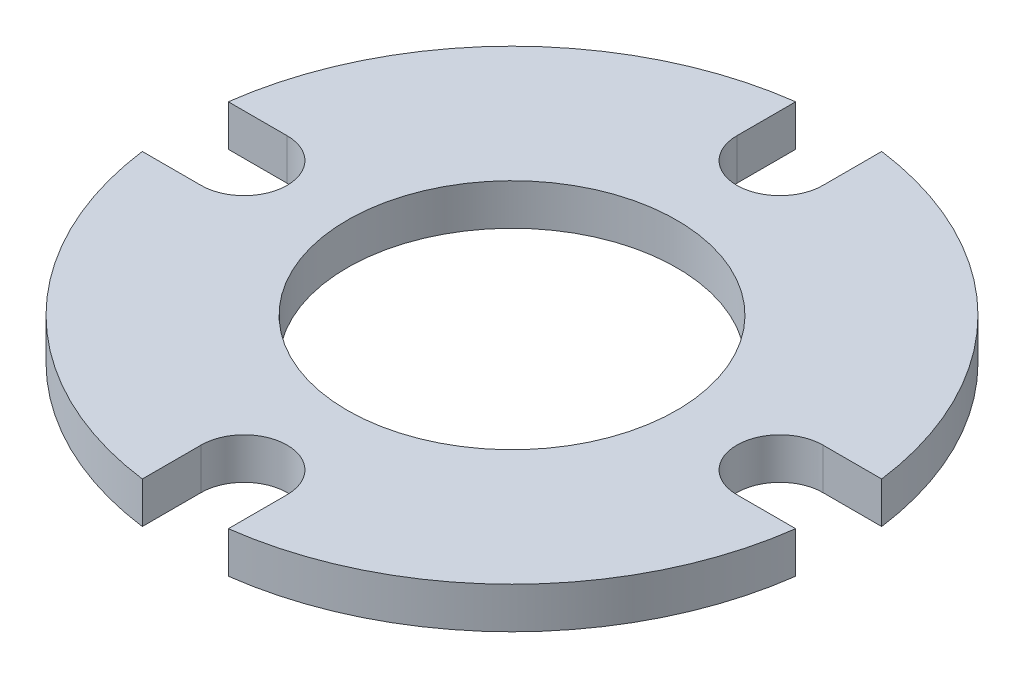
SolidWorks part; units mm, degrees
ref_plane "Front Plane" through (0, 0, 0) normal (0, 0, 1) x (1, 0, 0)
ref_plane "Top Plane" through (0, 0, 0) normal (0, 1, 0) x (1, 0, 0)
ref_plane "Right Plane" through (0, 0, 0) normal (1, 0, 0) x (0, 0, -1)
sketch "Sketch1" plane through (0, 0, 0) normal (0, 1, 0) x (1, 0, 0)
  line L0 (0, 0) -> (0, 1.6101) construction
  circle A0 centre (0, 0) radius 1
  dimension "D1" = 2
extrude "Boss-Extrude2" add sketch "Sketch1" along normal blind 0.125 contours A0
sketch "Sketch3" plane through (0, 0.125, 0) normal (0, 1, 0) x (1, 0, 0)
  line L0 (0, 0) -> (0, 1.0217) construction
  line L1 (-0.1306, 0.9914) -> (-0.1306, 0.813)
  line L2 (0.1306, 0.813) -> (0.1306, 0.9914)
  circle A0 centre (0, 0) radius 1 construction
  arc A1 (-0.1306, 0.813) -> (0.1306, 0.813) centre (0, 0.813) ccw
  point P9 (0, 0)
  dimension "D2" = 0.1306
  dimension "D1" = 0.813
extrude "Cut-Extrude1" cut sketch "Sketch3" against normal through all and the other way through all
pattern_circular "CirPattern1" count 4 over 360 about axis through (0, 0, 0) along (0, 1, 0) of "Cut-Extrude1"
sketch "Sketch4" plane through (0, 0.125, 0) normal (0, 1, 0) x (1, 0, 0)
  circle A0 centre (0, 0) radius 0.5
  dimension "D1" = 1
extrude "Cut-Extrude2" cut sketch "Sketch4" against normal through all
